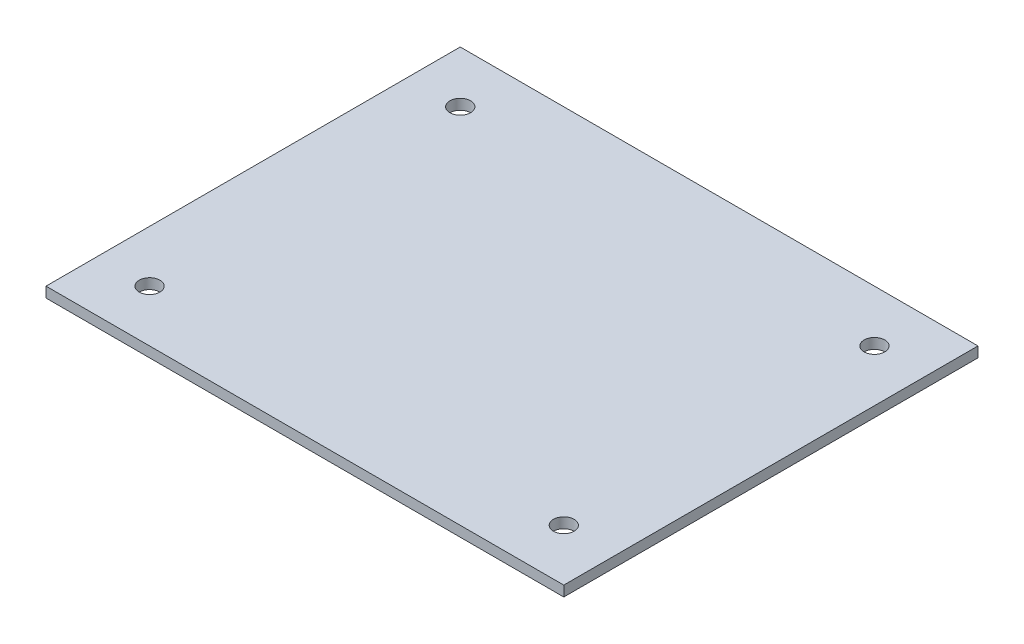
SolidWorks part; units mm, degrees
ref_plane "Front" through (0, 0, 0) normal (0, 0, 1) x (1, 0, 0)
ref_plane "Top" through (0, 0, 0) normal (0, 1, 0) x (1, 0, 0)
ref_plane "Right" through (0, 0, 0) normal (1, 0, 0) x (0, 0, -1)
sketch "Sketch1" plane through (0, 0, 0) normal (0, 1, 0) x (1, 0, 0)
  line L0 (0, 0) -> (-128.646, 0) construction
  line L5 (-125, 100) -> (125, 100)
  line L6 (-125, 100) -> (-125, -100)
  line L7 (-125, -100) -> (125, -100)
  line L8 (125, 100) -> (125, -100)
  line L9 (0, 0) -> (0, 100) construction
  line L10 (-87.1729, -31.3286) -> (-90.8865, -31.4428) construction
  line L11 (-90.0919, -36.3793) -> (-90.8865, -31.4428) construction
  line L12 (75.845, -36.845) -> (75.5776, -36.6214) construction
  line L13 (-90, 0) -> (-77.4344, 0) construction
  line L14 (-75.2357, -51.3853) -> (-66.4611, -50.7048) construction
  line L15 (-90.0919, -36.3793) -> (-86.3053, -35.7698) construction
  line L16 (-87.1696, -31.3285) -> (-90.8865, -31.4428) construction
  line L17 (-90.0919, -36.3793) -> (-90.8865, -31.4428) construction
  line L18 (-90.0919, -36.3793) -> (-86.2961, -35.7683) construction
  line L19 (-26.936, -78.9229) -> (-31.9353, -79.0035) construction
  line L20 (-32.0003, -74.971) -> (-31.9353, -79.0035) construction
  line L21 (-26.936, -78.9229) -> (-31.9353, -79.0035) construction
  line L22 (-32.0003, -74.971) -> (-31.9353, -79.0035) construction
  line L23 (-27.9763, -76.4321) -> (-26.9766, -76.4032) construction
  line L24 (-26.9766, -76.4032) -> (-26.936, -78.9229) construction
  line L25 (-27.9763, -76.4321) -> (-28.0019, -74.8419) construction
  line L26 (-27.9763, -76.4321) -> (-26.9766, -76.4032) construction
  line L27 (-26.9766, -76.4032) -> (-26.936, -78.9229) construction
  line L28 (-27.9763, -76.4321) -> (-28.0019, -74.8419) construction
  arc A0 (-90, 0) -> (-87.1696, -31.3285) centre (82.9375, -0.168) ccw construction
  arc A1 (-82.4604, -50.6749) -> (-78.4781, -55.1627) centre (-75.569, -48.5705) ccw construction
  arc A2 (-70.6654, -56.4296) -> (-72.5022, -56.2312) centre (-72.6533, -66.23) ccw construction
  arc A3 (-70.6654, -56.4296) -> (-62.6819, -65.4755) centre (-72.6534, -66.23) cw construction
  arc A4 (-78.4781, -55.1627) -> (-72.5022, -56.2312) centre (-73.2944, -43.4162) ccw construction
  arc A5 (75.7913, -28.3987) -> (75.7113, -36.7332) centre (80.0932, -32.6077) cw construction
  arc A6 (-62.6819, -65.4755) -> (-54.8607, -73.7223) centre (-53.7075, -64.7965) ccw construction
  arc A7 (-54.8607, -73.7223) -> (-32.0003, -74.971) centre (-35.0001, 80.0002) ccw construction
  arc A8 (-86, -0.0039) -> (-78.6348, -49.5067) centre (82.9375, -0.168) ccw construction
  arc A9 (-78.6348, -49.5067) -> (-76.8631, -51.5032) centre (-75.569, -48.5705) ccw construction
  arc A10 (-76.8631, -51.5032) -> (-72.6226, -52.2301) centre (-73.2944, -43.4162) ccw construction
  arc A11 (-69.8702, -52.5095) -> (-72.6226, -52.2301) centre (-72.6533, -66.23) ccw construction
  arc A12 (-69.8702, -52.5095) -> (-58.6933, -65.1737) centre (-72.6534, -66.23) cw construction
  arc A13 (-58.6933, -65.1737) -> (-54.3482, -69.7553) centre (-53.7075, -64.7965) ccw construction
  arc A14 (-54.3482, -69.7553) -> (72.9322, -25.6013) centre (-35.0001, 80.0002) ccw construction
  arc A15 (72.9322, -25.6013) -> (72.799, -39.4752) centre (80.0932, -32.6077) cw construction
  arc A16 (-77.4344, 0) -> (-64.0038, -46.5641) centre (10, 0) ccw construction
  arc A17 (-66.4611, -50.7048) -> (-64.0038, -46.5641) centre (-66.6886, -47.7703) ccw construction
  arc A18 (-75.2357, -51.3853) -> (-78.6348, -49.5067) centre (-75.5087, -47.8649) cw construction
  arc A19 (-86.2961, -35.7683) -> (-82.4604, -50.6749) centre (82.9375, -0.168) ccw construction
  arc A20 (-28.0019, -74.8419) -> (75.7913, -28.3987) centre (-35.0001, 80.0002) ccw construction
  arc A21 (-90, 0) -> (-82.4604, -50.6749) centre (82.9375, -0.168) ccw construction
  arc A23 (-54.8607, -73.7223) -> (75.7913, -28.3987) centre (-35.0001, 80.0002) ccw construction
  point P4 (125, 0)
  point P9 (0, 100)
  dimension "D1" = 200
  dimension "D2" = 250
  dimension "D3" = 4
extrude "Boss-Extrude1" add sketch "Sketch1" along normal blind 5
sketch "Sketch2" plane through (0, 5, 0) normal (0, 1, 0) x (1, 0, 0)
  line L0 (-90, 0) -> (-77.4344, 0) construction
  line L1 (-75.2357, -51.3853) -> (-66.4611, -50.7048) construction
  line L2 (-90, 0) -> (-77.4344, 0)
  line L3 (-72.6618, -51.1857) -> (-66.4611, -50.7048)
  line L4 (-90.0919, -36.3793) -> (-90.8865, -31.4428) construction
  line L5 (-90.0919, -36.3793) -> (-86.2961, -35.7683) construction
  line L6 (-87.1696, -31.3285) -> (-90.8865, -31.4428) construction
  line L7 (-90.0919, -36.3793) -> (-90.8865, -31.4428)
  line L8 (-90.0919, -36.3793) -> (-86.2961, -35.7683)
  line L9 (-87.1696, -31.3285) -> (-90.8865, -31.4428)
  line L10 (-26.936, -78.9229) -> (-31.9353, -79.0035) construction
  line L11 (-26.9766, -76.4032) -> (-26.936, -78.9229) construction
  line L12 (-27.9763, -76.4321) -> (-26.9766, -76.4032) construction
  line L13 (-27.9763, -76.4321) -> (-28.0019, -74.8419) construction
  line L15 (-26.936, -78.9229) -> (-31.9353, -79.0035)
  line L16 (-26.9766, -76.4032) -> (-26.936, -78.9229)
  line L17 (-27.9763, -76.4321) -> (-26.9766, -76.4032)
  line L18 (-27.9763, -76.4321) -> (-28.0019, -74.8419)
  line L20 (-32.0003, -74.971) -> (-31.9353, -79.0035)
  arc A0 (75.7113, -36.7332) -> (75.7913, -28.3987) centre (80.0932, -32.6077) ccw construction
  arc A2 (-62.6819, -65.4755) -> (-54.8607, -73.7223) centre (-53.7075, -64.7965) ccw construction
  arc A3 (-62.6819, -65.4755) -> (-70.6654, -56.4296) centre (-72.6534, -66.23) ccw construction
  arc A4 (-70.6654, -56.4296) -> (-72.5022, -56.2312) centre (-72.6533, -66.23) ccw construction
  arc A5 (-78.4781, -55.1627) -> (-72.5022, -56.2312) centre (-73.2944, -43.4162) ccw construction
  arc A6 (-82.4604, -50.6749) -> (-78.4781, -55.1627) centre (-75.569, -48.5705) ccw construction
  arc A8 (-77.4344, 0) -> (-64.0038, -46.5641) centre (10, 0) ccw construction
  arc A9 (-66.4611, -50.7048) -> (-64.0038, -46.5641) centre (-66.6886, -47.7703) ccw construction
  arc A10 (-86.2961, -35.7683) -> (-82.4604, -50.6749) centre (82.9375, -0.168) ccw
  arc A11 (75.7113, -36.7332) -> (75.7913, -28.3987) centre (80.0932, -32.6077) ccw
  arc A12 (-54.8607, -73.7223) -> (-32.0003, -74.971) centre (-35.0001, 80.0002) ccw
  arc A13 (-62.6819, -65.4755) -> (-54.8607, -73.7223) centre (-53.7075, -64.7965) ccw
  arc A14 (-62.6819, -65.4755) -> (-70.6654, -56.4296) centre (-72.6534, -66.23) ccw
  arc A15 (-70.6654, -56.4296) -> (-72.5022, -56.2312) centre (-72.6533, -66.23) ccw
  arc A16 (-78.4781, -55.1627) -> (-72.5022, -56.2312) centre (-73.2944, -43.4162) ccw
  arc A17 (-82.4604, -50.6749) -> (-78.4781, -55.1627) centre (-75.569, -48.5705) ccw
  arc A18 (-90, 0) -> (-87.1696, -31.3285) centre (82.9375, -0.168) ccw
  arc A19 (-77.4344, 0) -> (-64.0038, -46.5641) centre (10, 0) ccw
  arc A20 (-66.4611, -50.7048) -> (-64.0038, -46.5641) centre (-66.6886, -47.7703) ccw
  arc A22 (72.799, -39.4752) -> (72.9322, -25.6013) centre (80.0932, -32.6077) ccw construction
  arc A23 (-54.3482, -69.7553) -> (72.9322, -25.6013) centre (-35.0001, 80.0002) ccw construction
  arc A24 (-58.6933, -65.1737) -> (-54.3482, -69.7553) centre (-53.7075, -64.7965) ccw construction
  arc A25 (-58.6933, -65.1737) -> (-69.8702, -52.5095) centre (-72.6534, -66.23) ccw construction
  arc A26 (-69.8702, -52.5095) -> (-72.6226, -52.2301) centre (-72.6533, -66.23) ccw construction
  arc A27 (-28.0019, -74.8419) -> (75.7913, -28.3987) centre (-35.0001, 80.0002) ccw
  arc A28 (72.799, -39.4752) -> (72.9322, -25.6013) centre (80.0932, -32.6077) ccw
  arc A29 (-54.3482, -69.7553) -> (72.9322, -25.6013) centre (-35.0001, 80.0002) ccw
  arc A30 (-58.6933, -65.1737) -> (-54.3482, -69.7553) centre (-53.7075, -64.7965) ccw
  arc A31 (-58.6933, -65.1737) -> (-69.8702, -52.5095) centre (-72.6534, -66.23) ccw
  arc A32 (-69.8702, -52.5095) -> (-72.6226, -52.2301) centre (-72.6533, -66.23) ccw
  arc A34 (72.799, -39.4752) -> (75.7113, -36.7332) centre (74.2551, -38.1042) cw
  arc A37 (-72.6226, -52.2301) -> (-72.6618, -51.1857) centre (-72.6214, -51.7071) cw
  dimension "D1" = 0.523
extrude "Cut-Extrude1" [suppressed] cut sketch "Sketch2" against normal through all
mirror "Mirror1" [suppressed]
sketch "Sketch3" plane through (0, 0, 0) normal (0, 1, 0) x (1, 0, 0)
  line L0 (0, 0) -> (-155.8079, 0) construction
  line L1 (0, 0) -> (0, 127.5715) construction
  circle A0 centre (-100, 75) radius 5
  circle A1 centre (100, 75) radius 5
  circle A2 centre (100, -75) radius 5
  circle A3 centre (-100, -75) radius 5
  dimension "D1" = 10
  dimension "D2" = 150
  dimension "D3" = 200
extrude "holes" cut sketch "Sketch3" along normal through all
sketch "Sketch4" [suppressed] plane through (0, 5, 0) normal (0, 1, 0) x (1, 0, 0)
  line L0 (-90, 0) -> (-77.4344, 0) construction
  circle A0 centre (-83.7172, 0) radius 2.5
  dimension "D1" = 5
extrude "Cut-Extrude2" [suppressed] cut sketch "Sketch4" against normal through all
